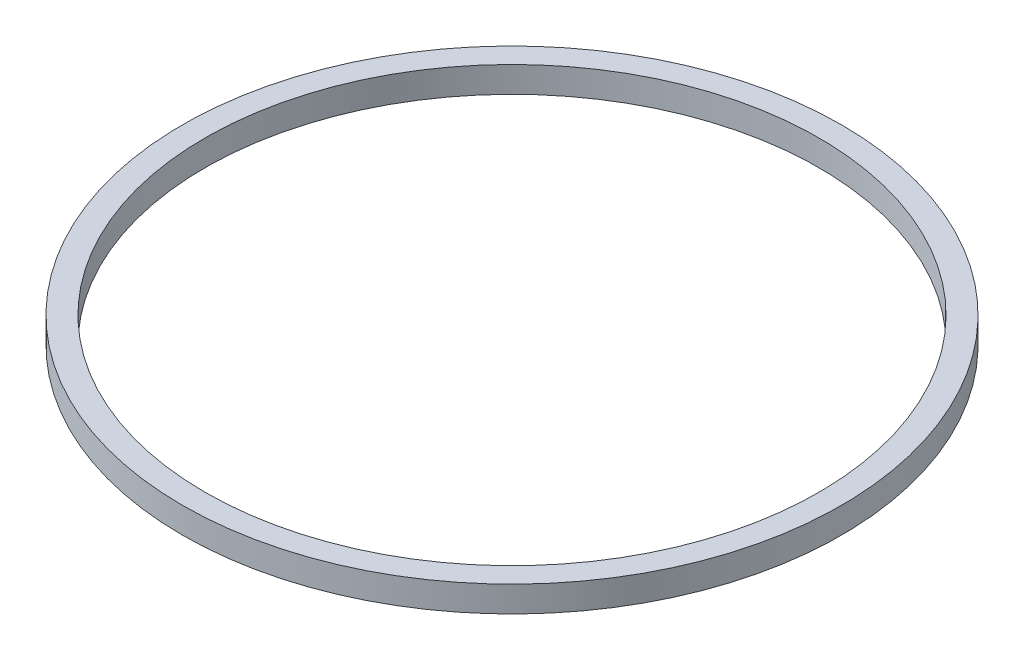
SolidWorks part; units mm, degrees
ref_plane "前视基准面" through (0, 0, 0) normal (0, 0, 1) x (1, 0, 0)
ref_plane "上视基准面" through (0, 0, 0) normal (0, 1, 0) x (1, 0, 0)
ref_plane "右视基准面" through (0, 0, 0) normal (1, 0, 0) x (0, 0, -1)
sketch "草图1" plane through (0, 0, 0) normal (0, 1, 0) x (1, 0, 0)
  circle A0 centre (0, 0) radius 102
  circle A1 centre (0, 0) radius 95
  dimension "D1" = 204
  dimension "D2" = 190
extrude "凸台-拉伸1" add sketch "草图1" along normal blind 8
